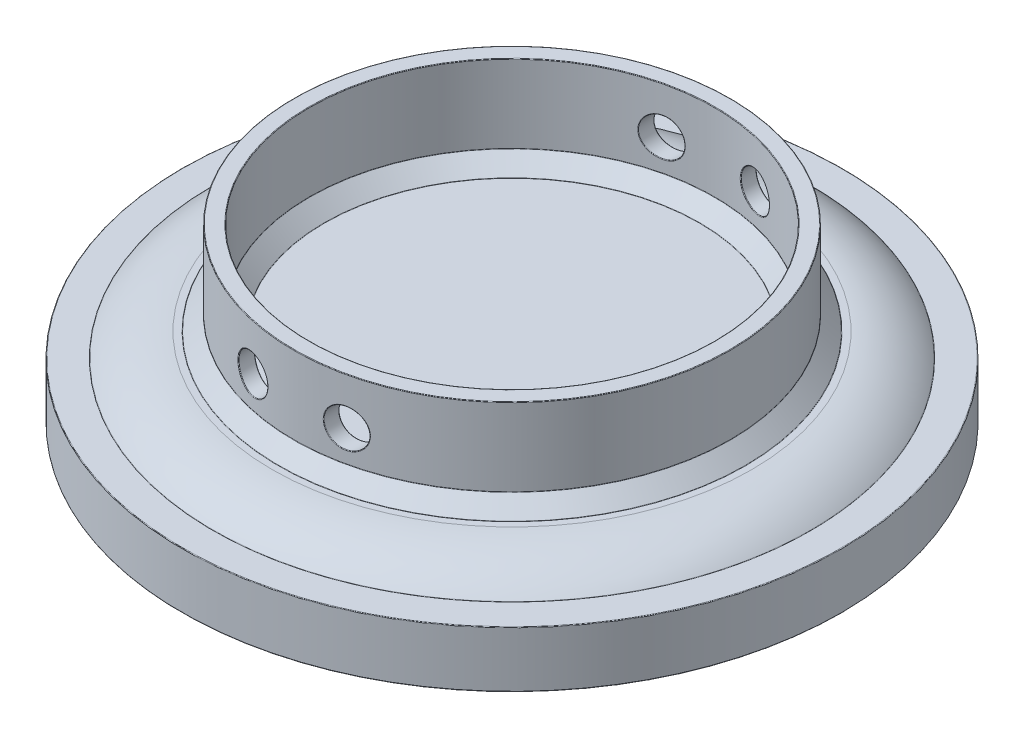
SolidWorks part; units mm, degrees
material "PET"
ref_plane "Front Plane" through (0, 0, 0) normal (0, 0, 1) x (1, 0, 0)
ref_plane "Top Plane" through (0, 0, 0) normal (0, 1, 0) x (1, 0, 0)
ref_plane "Right Plane" through (0, 0, 0) normal (1, 0, 0) x (0, 0, -1)
sketch "Sketch1" plane through (0, 0, 0) normal (0, 0, 1) x (1, 0, 0)
  line L0 (0, 0) -> (0, 42.4) construction
  line L1 (0, 30) -> (128.03, 30)
  line L2 (151.8853, 20.1178) -> (172, 0)
  line L3 (176, 0) -> (176, 30)
  line L4 (0, 42.4) -> (128.03, 42.4)
  line L5 (176, 30) -> (159.5, 30)
  line L6 (0, 42.4) -> (0, 30)
  line L7 (116.5, 50.4) -> (124.5, 42.4)
  line L8 (108.2, 92) -> (116.5, 92)
  line L9 (108.2, 92) -> (108.2, 50.4)
  line L10 (108.2, 50.4) -> (116.5, 50.4)
  line L11 (116.5, 92) -> (116.5, 50.4)
  line L12 (108.2, 50.4) -> (100.2, 42.4)
  line L13 (172, 0) -> (176, 0)
  arc A0 (128.03, 30) -> (151.8853, 20.1178) centre (128.03, -3.7339) cw
  arc A1 (128.03, 42.4) -> (159.5, 30) centre (128.03, -3.7339) cw
  dimension "D1" = 12.4
  dimension "D2" = 352
  dimension "D3" = 30
  dimension "D4" = 128.03
  dimension "D5" = 4
  dimension "D6" = 16.5
  dimension "D7" = 233
  dimension "D8" = 8.3
  dimension "D9" = 45
  dimension "D10" = 45
  dimension "D11" = 8
  dimension "D12" = 92
revolve "Revolve1" add sketch "Sketch1" angle 360 about L0
sketch "Sketch2" plane through (0, 0, 0) normal (0, 0, 1) x (1, 0, 0)
  line L0 (-116.5, 67) -> (116.5, 67) construction
  line L1 (116.5, 50.4) -> (116.5, 92) construction
  line L2 (-116.5, 92) -> (-116.5, 50.4) construction
  line L3 (116.5, 92) -> (-116.5, 92) construction
  circle A0 centre (25, 67) radius 10
  circle A1 centre (-25, 67) radius 10
  dimension "D2" = 20
  dimension "D1" = 25
  dimension "D3" = 25
  dimension "D4" = 25
extrude "Cut-Extrude1" cut sketch "Sketch2" against normal through all both and the other way through all contours A1 | A0
fillet "Fillet1" radius 0.3 18 edges at (100.2, 42.4, 0) (172, 0, 0) (108.2, 50.4, 0) (-34.7344, 64.7106, -102.4732) (-34.7344, 69.2894, 102.4732) (15.2394, 64.8252, -107.1214) (15.2394, 69.1748, 107.1214) (-34.7343, 64.71, -111.2015) (-34.7343, 69.29, 111.2015) (15.243, 64.8087, -115.4985) (15.243, 69.1913, 115.4985) (176, 0, 0) (176, 30, 0) (159.5, 30, 0) (116.5, 50.4, 0) (124.5, 42.4, 0) (108.2, 92, 0) (116.5, 92, 0)
